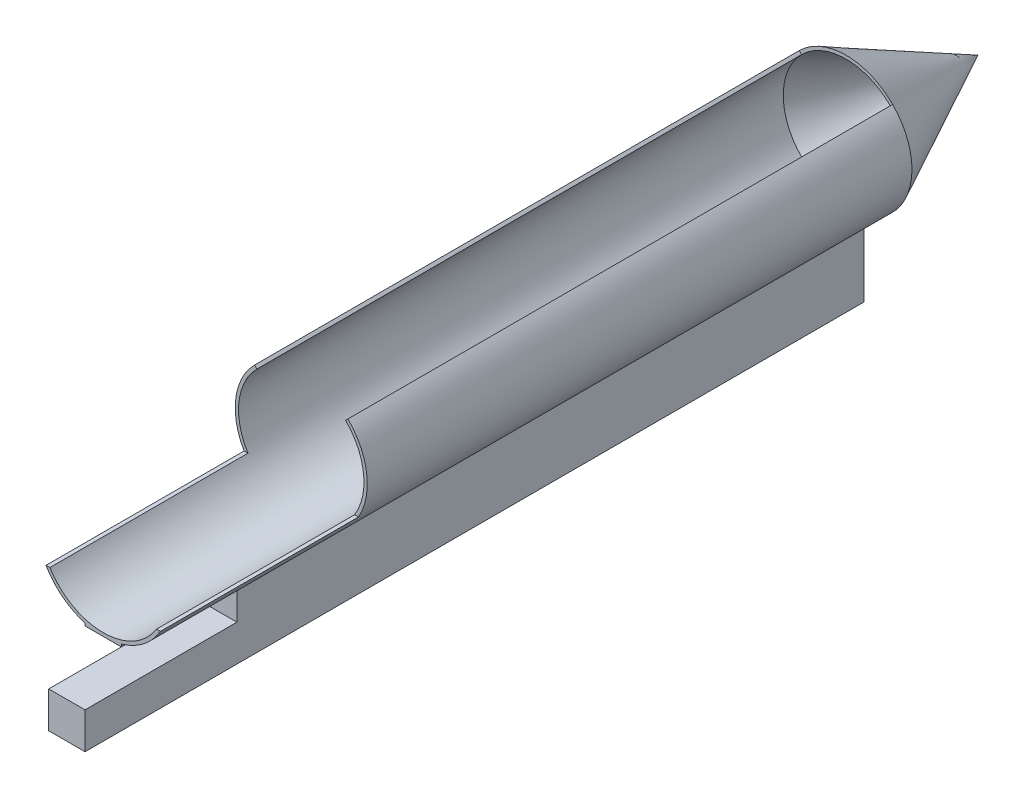
SolidWorks part; units mm, degrees
ref_plane "Plan de face" through (0, 0, 0) normal (0, 0, 1) x (1, 0, 0)
ref_plane "Plan de dessus" through (0, 0, 0) normal (0, 1, 0) x (1, 0, 0)
ref_plane "Plan de droite" through (0, 0, 0) normal (1, 0, 0) x (0, 0, -1)
sketch "Esquisse1" plane through (0, 0, 0) normal (0, 0, 1) x (1, 0, 0)
  line L0 (0, 0) -> (0, -84) construction
  line L1 (0, 0) -> (-28.2843, 28.2843) construction
  line L2 (0, 0) -> (28.2843, 28.2843) construction
  line L3 (-11, -38.4578) -> (-11, -84)
  line L4 (-11, -84) -> (11, -84)
  line L5 (11, -38.4578) -> (11, -84)
  line L6 (-28.2843, 28.2843) -> (-26.8701, 26.8701)
  line L7 (26.8701, 26.8701) -> (28.2843, 28.2843)
  arc A0 (11, -38.4578) -> (28.2843, 28.2843) centre (0, 0) ccw
  arc A1 (-26.8701, 26.8701) -> (26.8701, 26.8701) centre (0, 0) ccw
  arc A2 (-28.2843, 28.2843) -> (-11, -38.4578) centre (0, 0) ccw
  point P3 (0, -40)
  point P6 (0, -84)
  point P10 (0, 0)
  dimension "D1" = 80
  dimension "D4" = 76
  dimension "D2" = 22
  dimension "D3" = 44
  dimension "D5" = 90
  dimension "D6" = 135
extrude "Boss.-Extru.1" add sketch "Esquisse1" along normal blind 472
sketch "Esquisse2" plane through (0, 0, 472) normal (0, 0, 1) x (1, 0, 0)
  line L0 (82.5, 62) -> (82.5, -62)
  line L1 (82.5, 62) -> (-82.5, 62)
  line L2 (82.5, -62) -> (-82.5, -62)
  line L3 (-82.5, 62) -> (-82.5, -62)
  line L4 (82.5, 62) -> (-82.5, -62) construction
  line L5 (82.5, -62) -> (-82.5, 62) construction
  line L6 (-11, -84) -> (11, -84) construction
  point P1 (0, 0)
  dimension "D1" = 22
  dimension "D2" = 165
extrude "Enlèv. mat.-Extru.1" cut sketch "Esquisse2" against normal blind 22
sketch "Esquisse3" plane through (0, 0, 450) normal (0, 0, 1) x (1, 0, 0)
  line L0 (0, 0) -> (0, -6.3788) construction
  line L1 (0, -100.8816) -> (0, -3.1894) construction
  line L2 (-11, -62) -> (11, -62) construction
  line L3 (-25, -40) -> (25, -40)
  line L4 (-25, -40) -> (-25, -62)
  line L5 (-25, -62) -> (25, -62)
  line L6 (25, -40) -> (25, -62)
  line L7 (-11, -62) -> (11, -62) construction
  point P5 (0, -40)
  dimension "D1" = 40
  dimension "D2" = 0
  dimension "D3" = 50
extrude "Enlèv. mat.-Extru.2" cut sketch "Esquisse3" against normal blind 70
sketch "Esquisse4" plane through (0, 0, 450) normal (0, 0, 1) x (1, 0, 0)
  line L0 (-67.5, 20) -> (-67.5, -20)
  line L2 (-67.5, -20) -> (67.5, -20)
  line L3 (67.5, 20) -> (67.5, -20)
  line L4 (-67.5, 20) -> (67.5, -20) construction
  line L5 (-67.5, -20) -> (67.5, 20) construction
  line L6 (11, -40) -> (-11, -40) construction
  line L8 (-67.5, 20) -> (-67.5, 60)
  line L9 (67.5, 20) -> (67.5, 60)
  line L10 (-67.5, 60) -> (67.5, 60)
  point P1 (0, 0)
  dimension "D1" = 20
  dimension "D2" = 135
  dimension "D3" = 40
extrude "Enlèv. mat.-Extru.3" cut sketch "Esquisse4" against normal blind 120 contours L10 L9 L3 L2 L0 L8
sketch3d "Esquisse3D1"
  line L0 (0, 0, 0) -> (0, 0, -80) construction
  dimension "D1" = 80
sketch "Esquisse6" plane through (0, 0, 0) normal (0, 1, 0) x (1, 0, 0)
  line L0 (0, 80) -> (-40, 0)
  line L1 (0, 0) -> (0, 80) construction
  line L2 (-11, 0) -> (11, 0) construction
  line L3 (0, 76) -> (-38, 0)
  line L4 (-38, 0) -> (-40, 0)
  line L5 (0, 80) -> (0, 76)
  point P4 (0, 76)
  dimension "D1" = 76
revolve "Révolution1" add sketch "Esquisse6" angle 360 about L0
